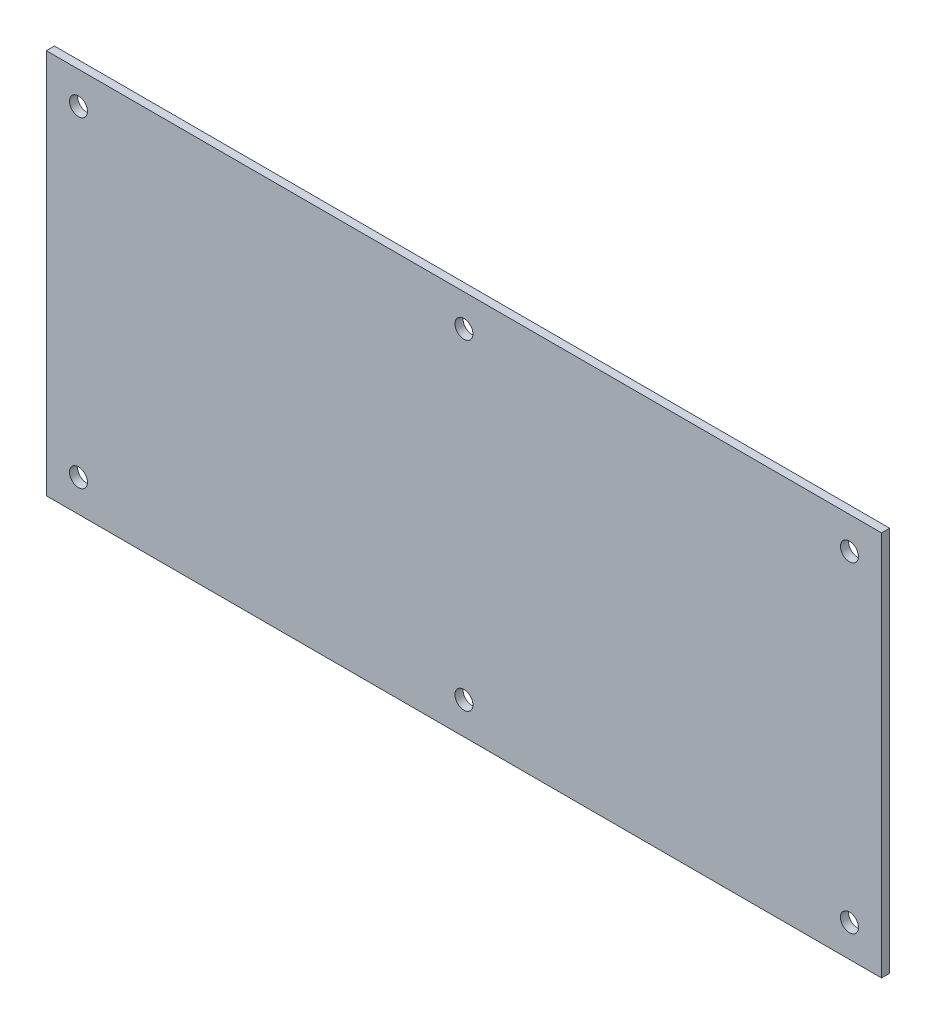
SolidWorks part; units mm, degrees
ref_plane "front" through (0, 0, 0) normal (0, 0, 1) x (1, 0, 0)
ref_plane "top" through (0, 0, 0) normal (0, 1, 0) x (1, 0, 0)
ref_plane "right" through (0, 0, 0) normal (1, 0, 0) x (0, 0, -1)
sketch "Sketch1" plane through (0, 0, 0) normal (0, 0, 1) x (1, 0, 0)
  line L1 (0, 0) -> (165.1, 0)
  line L2 (0, 0) -> (0, 76.2)
  line L3 (0, 76.2) -> (165.1, 76.2)
  line L4 (165.1, 0) -> (165.1, 76.2)
  dimension "D1" = 76.2
  dimension "D2" = 165.1
extrude "Extrude1" add sketch "Sketch1" against normal blind 1.6002
sketch "Sketch2" plane through (0, 0, 0) normal (0, 0, 1) x (1, 0, 0)
  line L0 (165.1, 0) -> (165.1, 76.2) construction
  line L1 (165.1, 76.2) -> (0, 76.2) construction
  circle A0 centre (6.35, 69.85) radius 1.778
  circle A1 centre (158.75, 69.85) radius 1.778
  circle A2 centre (158.75, 6.35) radius 1.778
  circle A3 centre (6.35, 6.35) radius 1.778
  circle A4 centre (82.55, 6.35) radius 1.778
  circle A5 centre (82.55, 69.85) radius 1.778
  dimension "D2" = 3.556
  dimension "D1" = 6.35
  dimension "D3" = 76.2
  dimension "D4" = 76.2
  dimension "D5" = 6.35
  dimension "D6" = 6.35
  dimension "D7" = 63.5
  dimension "D8" = 6.35
extrude "Cut-Extrude1" cut sketch "Sketch2" against normal blind 2.54
